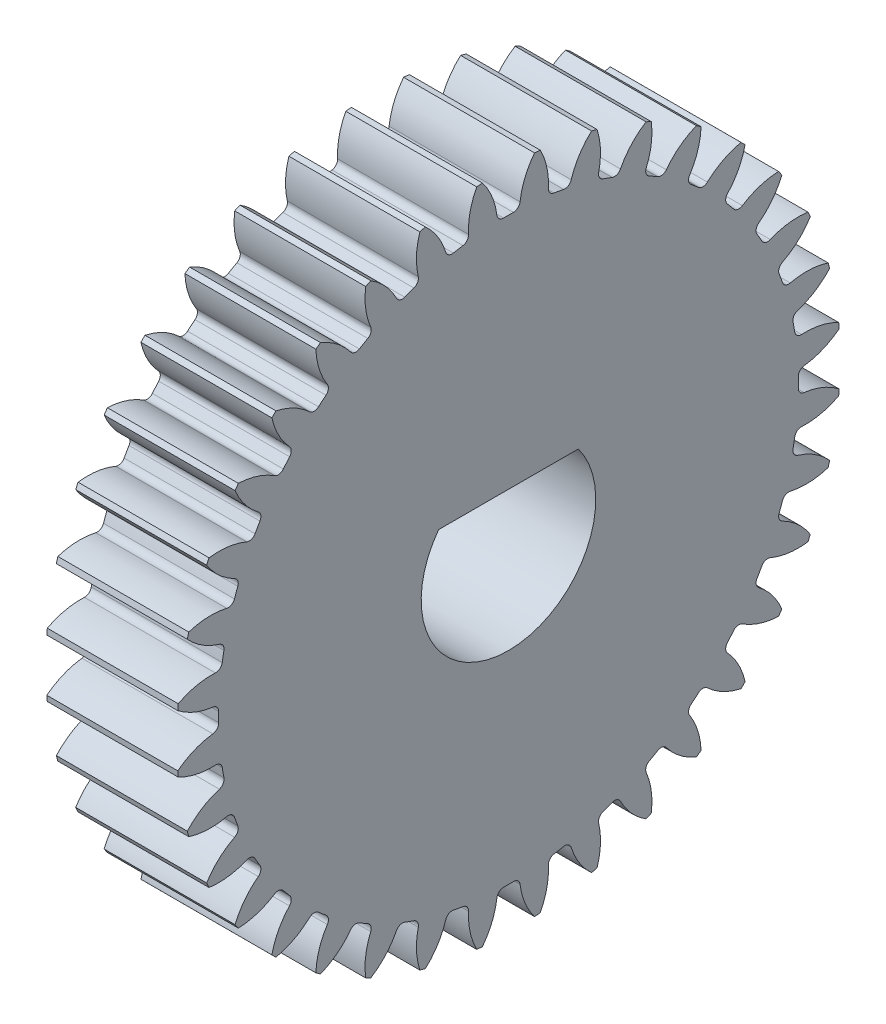
SolidWorks part; units mm, degrees
ref_plane "Front Plane" through (0, 0, 0) normal (0, 0, 1) x (1, 0, 0)
ref_plane "Top Plane" through (0, 0, 0) normal (0, 1, 0) x (1, 0, 0)
ref_plane "Right Plane" through (0, 0, 0) normal (1, 0, 0) x (0, 0, -1)
sketch "Sketch1" plane through (0, 0, 0) normal (1, 0, 0) x (0, 0, -1)
  circle A0 centre (0, 0) radius 5
  circle A1 centre (0, 0) radius 19
  dimension "D1" = 10
  dimension "D2" = 38
extrude "Boss-Extrude2" add sketch "Sketch1" along normal blind 7.5
sketch "Sketch3" plane through (7.5, 0, 0) normal (1, 0, 0) x (0, 0, -1)
  line L0 (0, 0) -> (0, 19) construction
  line L1 (-0.6359, 16.5878) -> (0, 0) construction
  line L2 (0, 15.4142) -> (-2.2129, 21.4942) construction
  circle A0 centre (0, 0) radius 19 construction
  arc A1 (0.6359, 16.5878) -> (-0.6359, 16.5878) centre (0, 0) ccw
  arc A2 (0.9354, 17.9757) -> (-0.9354, 17.9757) centre (0, 0) ccw construction
  arc A3 (1.4925, 18.9413) -> (-1.4925, 18.9413) centre (0, 0) ccw
  arc A4 (-1.4925, 18.9413) -> (-0.6359, 16.5878) centre (-4.7283, 16.4309) cw
  arc A5 (1.4925, 18.9413) -> (0.6359, 16.5878) centre (4.7283, 16.4309) ccw
  point P17 (-0.8799, 17.8316)
  dimension "D1" = 38
  dimension "D2" = 36
  dimension "D3" = 2.4
  dimension "D4" = 20
  dimension "D5" = 1.8708
extrude "Cut-Extrude1" cut sketch "Sketch3" against normal through all
fillet "Fillet1" radius 0.38 2 edges at (3.75, 16.5878, -0.6359) (3.75, 16.5878, 0.6359)
pattern_circular "CirPattern2" count 36 over 360 about axis through (0, 0, 0) along (1, 0, 0) of "Fillet1", "Cut-Extrude1"
sketch "Sketch4" plane through (7.5, 0, 0) normal (1, 0, 0) x (0, 0, -1)
  line L0 (-4, 3) -> (4, 3)
  circle A0 centre (0, 0) radius 5 construction
  arc A1 (-4, 3) -> (4, 3) centre (0, 0) cw
  dimension "D1" = 3
extrude "Boss-Extrude3" add sketch "Sketch4" against normal up to surface (7.5 mm away) up to face at (0, 0, -5)
equation "\"No of teeth\"= 36"
equation "\"Module\"= 1"
equation "\"Outer Diameter\"= ( \"No of teeth\" + 2 ) * \"Module\""
equation "\"Pitch Diameter\"= \"No of teeth\" * \"Module\""
equation "\"Backlash\"= 0.3 * \"Module\""
equation "\"Arc Length\"= ( ( \"Module\" * pi ) / 2 ) + \"Backlash\""
equation "\"Fillet Radius\"= 0.38 * \"Module\""
equation "\"Bore Diameter\"=10"
equation "\"Presseure angle\"= 20"
equation "\"Tooth Depth\"= IIF ( \"Module\" <= 1.25 , 2.4 * \"Module\" , 2.25 * \"Module\" )"
equation "\"D1@Sketch1\"=\"Bore Diameter\""
equation "\"D2@Sketch1\"=\"Outer Diameter\""
equation "\"D1@Sketch3\"=\"Outer Diameter\""
equation "\"D2@Sketch3\"=\"Pitch Diameter\""
equation "\"D3@Sketch3\"=\"Tooth Depth\""
equation "\"D4@Sketch3\"=\"Presseure angle\""
equation "\"D5@Sketch3\"=\"Arc Length\""
equation "\"D1@Fillet1\"=\"Fillet Radius\""
equation "\"D1@CirPattern2\"=\"No of teeth\""
